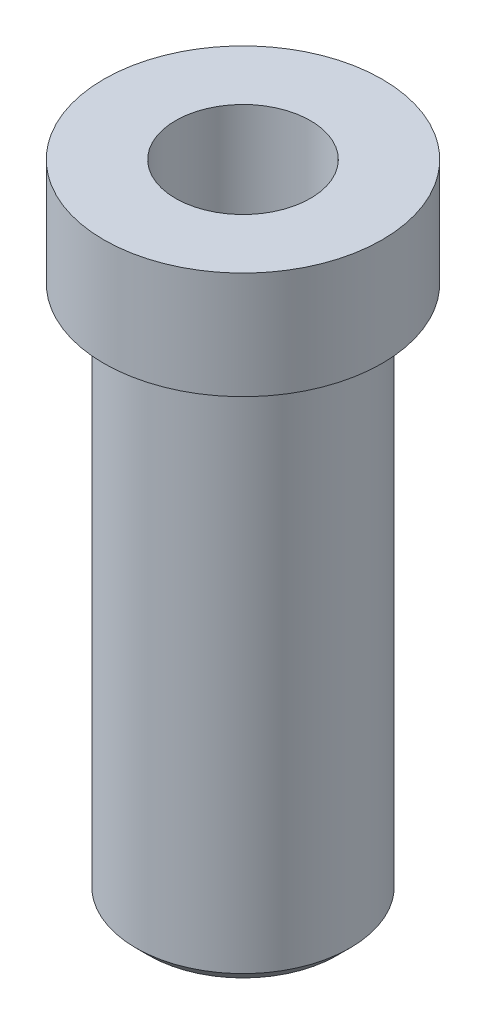
SolidWorks part; units mm, degrees
ref_plane "Front Plane" through (0, 0, 0) normal (0, 0, 1) x (1, 0, 0)
ref_plane "Top Plane" through (0, 0, 0) normal (0, 1, 0) x (1, 0, 0)
ref_plane "Right Plane" through (0, 0, 0) normal (1, 0, 0) x (0, 0, -1)
sketch "Sketch1" plane through (0, 0, 0) normal (0, 0, 1) x (1, 0, 0)
  line L0 (0, 0) -> (0, 3)
  line L1 (0, 3) -> (0.65, 3)
  line L2 (0.65, 3) -> (0.65, 2.5)
  line L3 (0.65, 2.5) -> (0.5, 2.5)
  line L4 (0.5, 2.5) -> (0.5, 0)
  line L5 (0.5, 0) -> (0, 0)
  dimension "D1" = 3
  dimension "D2" = 0.5
  dimension "D3" = 0.65
  dimension "D4" = 0.5
revolve "Revolve1" add sketch "Sketch1" angle 360 about L0
sketch "Sketch2" plane through (0, 3, 0) normal (0, 1, 0) x (1, 0, 0)
  circle A0 centre (0, 0) radius 0.315
  dimension "D1" = 0.63
extrude "Cut-Extrude1" cut sketch "Sketch2" against normal through all
chamfer "Chamfer1" distance 0.06 angle 45 1 edges at (0, 0, -0.5)
